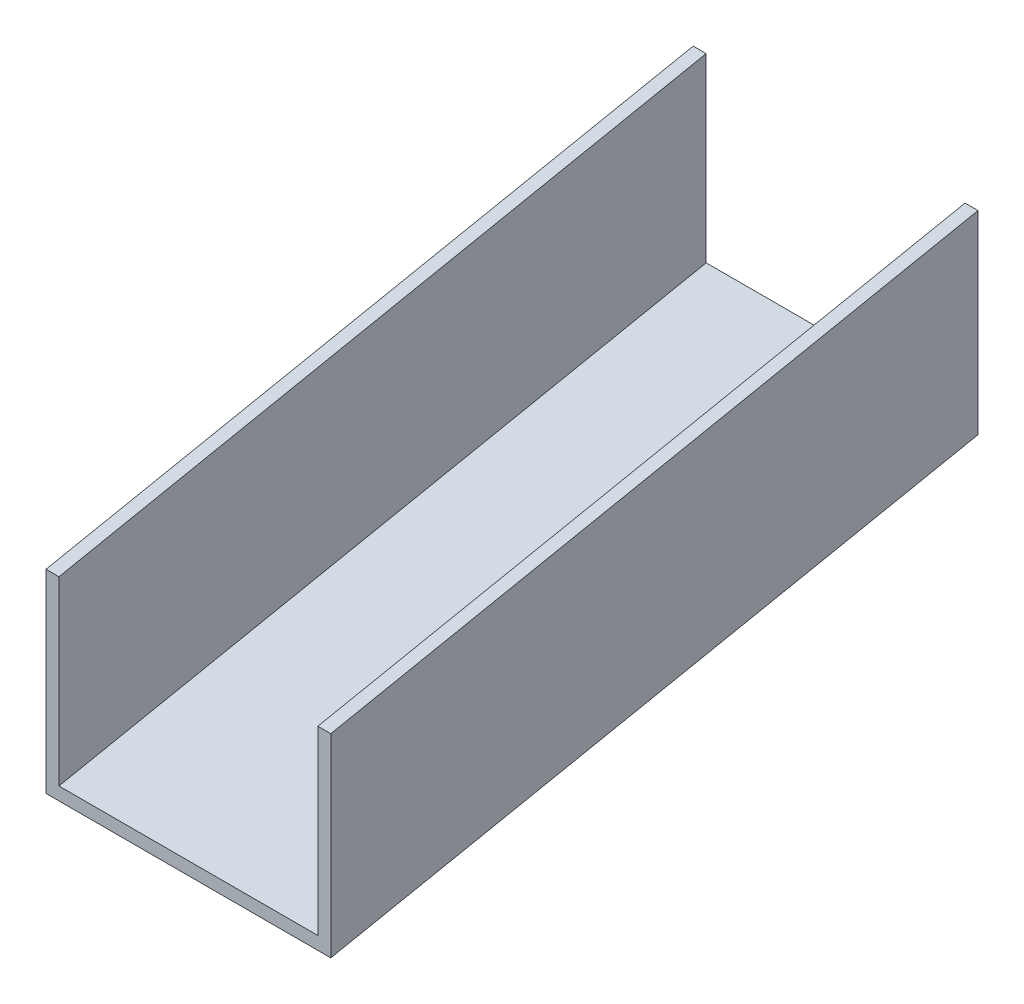
SolidWorks part; units mm, degrees
ref_plane "Front Plane" through (0, 0, 0) normal (0, 0, 1) x (1, 0, 0)
ref_plane "Top Plane" through (0, 0, 0) normal (0, 1, 0) x (1, 0, 0)
ref_plane "Right Plane" through (0, 0, 0) normal (1, 0, 0) x (0, 0, -1)
sketch "Sketch1" plane through (0, 0, 0) normal (0, 0, 1) x (1, 0, 0)
  line L0 (44, 30) -> (44, 0)
  line L1 (44, 0) -> (0, 0)
  line L2 (0, 0) -> (0, 30)
  line L3 (0, 30) -> (2, 30)
  line L4 (2, 30) -> (2, 2)
  line L5 (2, 2) -> (42, 2)
  line L6 (42, 2) -> (42, 30)
  line L7 (42, 30) -> (44, 30)
  dimension "D1" = 2
  dimension "D2" = 2
  dimension "D3" = 2
  dimension "D4" = 30
  dimension "D5" = 40
ref_plane "Plane1" through (0, 0, 100) normal (0, 0, 1) x (1, 0, 0)
sketch "Sketch2" plane through (0, 0, 100) normal (0, 0, 1) x (1, 0, 0)
  line L0 (44, 10) -> (44, -20)
  line L1 (44, -20) -> (0, -20)
  line L2 (0, -20) -> (0, 10)
  line L3 (0, 10) -> (2, 10)
  line L4 (2, 10) -> (2, -18)
  line L5 (2, -18) -> (42, -18)
  line L6 (42, -18) -> (42, 10)
  line L7 (42, 10) -> (44, 10)
  line L16 (22, 0) -> (22, -20) construction
  line L24 (44, 0) -> (44, 30)
  line L25 (0, 0) -> (44, 0)
  line L26 (0, 30) -> (0, 0)
  line L27 (2, 30) -> (0, 30)
  line L28 (2, 2) -> (2, 30)
  line L29 (42, 2) -> (2, 2)
  line L30 (42, 30) -> (42, 2)
  line L31 (44, 30) -> (42, 30)
  line L32 (44, 0) -> (44, 30) construction
  line L33 (0, 0) -> (44, 0) construction
  line L34 (0, 30) -> (0, 0) construction
  line L35 (2, 30) -> (0, 30) construction
  line L36 (2, 2) -> (2, 30) construction
  line L37 (42, 2) -> (2, 2) construction
  line L38 (42, 30) -> (42, 2) construction
  line L39 (44, 30) -> (42, 30) construction
  dimension "D2" = 2
  dimension "D3" = 2
  dimension "D5" = 40
  dimension "D4" = 2
  dimension "D6" = 30
  dimension "D7" = 20
loft "Loft3" add profiles "Sketch2", "Sketch1"
equation "\"SlideWallThickness\"=2"
equation "\"D1@Sketch1\"=\"SlideWallThickness\""
equation "\"D2@Sketch1\"=\"SlideWallThickness\""
equation "\"D3@Sketch1\"=\"SlideWallThickness\""
equation "\"SlideWallHeight\"=30"
equation "\"D4@Sketch1\"=\"SlideWallHeight\""
equation "\"SlideInnerWidth\"=40"
equation "\"D5@Sketch1\"=\"SlideInnerWidth\""
equation "\"D2@Sketch2\"=\"SlideWallThickness\""
equation "\"D3@Sketch2\"=\"SlideWallThickness\""
equation "\"D4@Sketch2\"=\"SlideWallThickness\""
equation "\"D5@Sketch2\"=\"SlideInnerWidth\""
equation "\"D6@Sketch2\"=\"SlideWallHeight\""
equation "\"SlideVirticalHead\"=20"
equation "\"D7@Sketch2\"=\"SlideVirticalHead\""
